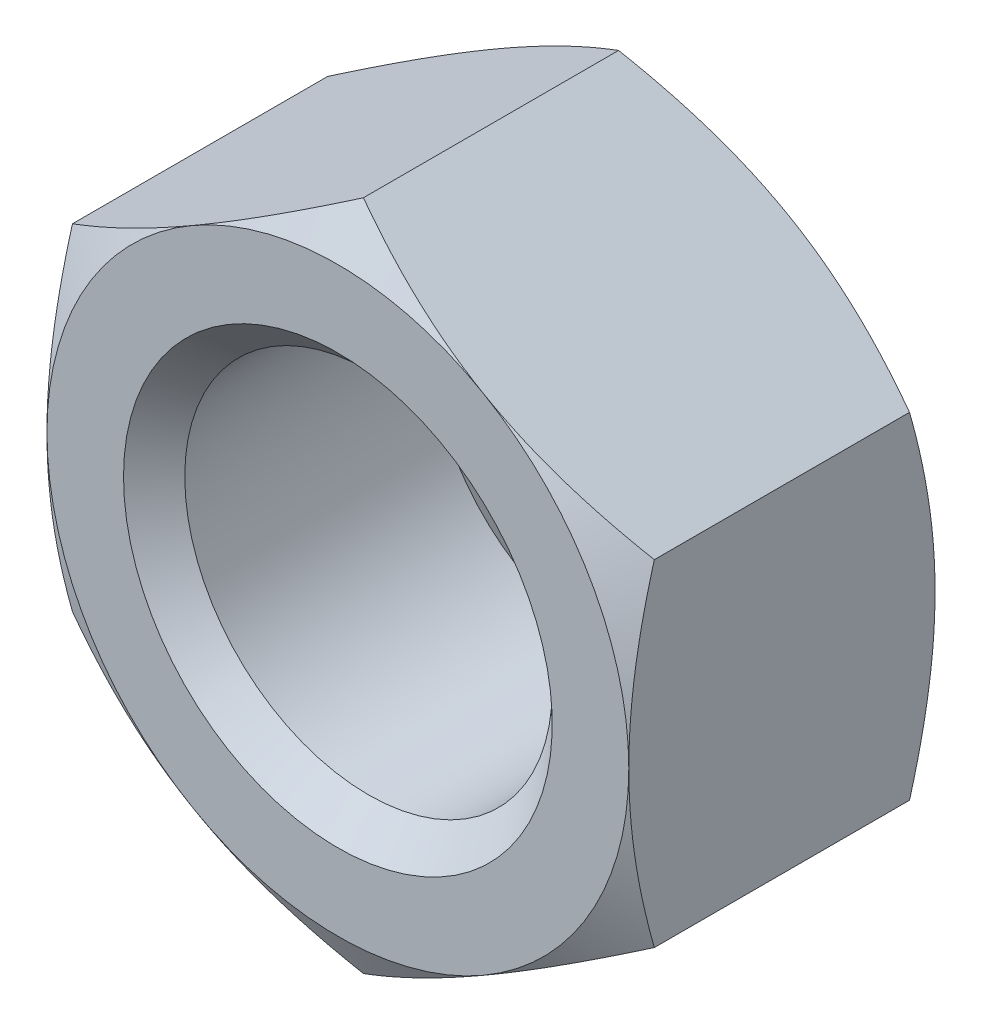
SolidWorks part; units mm, degrees
material "Plain Carbon Steel"
ref_plane "Front Plane" through (0, 0, 0) normal (0, 0, 1) x (1, 0, 0)
ref_plane "Top Plane" through (0, 0, 0) normal (0, 1, 0) x (1, 0, 0)
ref_plane "Right Plane" through (0, 0, 0) normal (1, 0, 0) x (0, 0, -1)
sketch "Sketch1" plane through (0, 0, 0) normal (0, 0, 1) x (1, 0, 0)
  line L1 (0, -10.9697) -> (9.5, -5.4848)
  line L2 (9.5, -5.4848) -> (9.5, 5.4848)
  line L3 (9.5, 5.4848) -> (0, 10.9697)
  line L4 (0, 10.9697) -> (-9.5, 5.4848)
  line L5 (-9.5, 5.4848) -> (-9.5, -5.4848)
  line L6 (-9.5, -5.4848) -> (0, -10.9697)
  circle A0 centre (0, 0) radius 9.5 construction
  circle A1 centre (0, 0) radius 6
  dimension "D2" = 12
  dimension "D1" = 19
extrude "Boss-Extrude1" add sketch "Sketch1" along normal blind 10
sketch "Sketch2" plane through (0, 0, 0) normal (1, 0, 0) x (0, 0, -1)
  line L0 (-10, 10.9697) -> (-10, 9.5)
  line L1 (-10, 5.4848) -> (-10, 10.9697) construction
  line L2 (-10, 9.5) -> (-9.1667, 10.9697)
  line L3 (-10, 10.9697) -> (0, 10.9697) construction
  line L4 (-9.1667, 10.9697) -> (-10, 10.9697)
  line L5 (-0.8333, 10.9697) -> (0, 10.9697)
  line L6 (0, 10.9697) -> (0, 9.5)
  line L7 (0, 5.4848) -> (0, 10.9697) construction
  line L8 (0, 9.5) -> (-0.8333, 10.9697)
  line L9 (-9.1667, 10.9697) -> (-8.3333, 10.9697) construction
  line L10 (-8.3333, 10.9697) -> (-7.5, 10.9697) construction
  line L11 (-7.5, 10.9697) -> (-6.6667, 10.9697) construction
  line L12 (-6.6667, 10.9697) -> (-5.8333, 10.9697) construction
  line L13 (-5.8333, 10.9697) -> (-5, 10.9697) construction
  line L14 (-5, 10.9697) -> (-4.1667, 10.9697) construction
  line L15 (-4.1667, 10.9697) -> (-3.3333, 10.9697) construction
  line L16 (-3.3333, 10.9697) -> (-2.5, 10.9697) construction
  line L17 (-2.5, 10.9697) -> (-1.6667, 10.9697) construction
  line L18 (0, 0) -> (-10, 0) construction
  line L19 (-10, -5.4848) -> (-10, 5.4848) construction
  line L20 (-10, 6) -> (-9, 6)
  line L21 (-9, 6) -> (-10, 7)
  line L22 (-10, 7) -> (-10, 6)
  line L23 (0, 6) -> (-1, 6)
  line L24 (0, -5.4848) -> (0, 5.4848) construction
  line L25 (-1, 6) -> (0, 7)
  line L26 (0, 7) -> (0, 6)
  line L29 (-9, 6) -> (-8, 6) construction
  line L30 (-8, 6) -> (-7, 6) construction
  line L31 (-7, 6) -> (-6, 6) construction
  line L32 (-6, 6) -> (-5, 6) construction
  line L33 (-5, 6) -> (-4, 6) construction
  line L34 (-4, 6) -> (-3, 6) construction
  line L35 (-3, 6) -> (-2, 6) construction
  line L36 (-2, 6) -> (-1, 6) construction
  line L37 (-1.6667, 10.9697) -> (-0.8333, 10.9697) construction
  dimension "D1" = 19
revolve "Cut-Revolve1" cut sketch "Sketch2" angle 360 about L18
